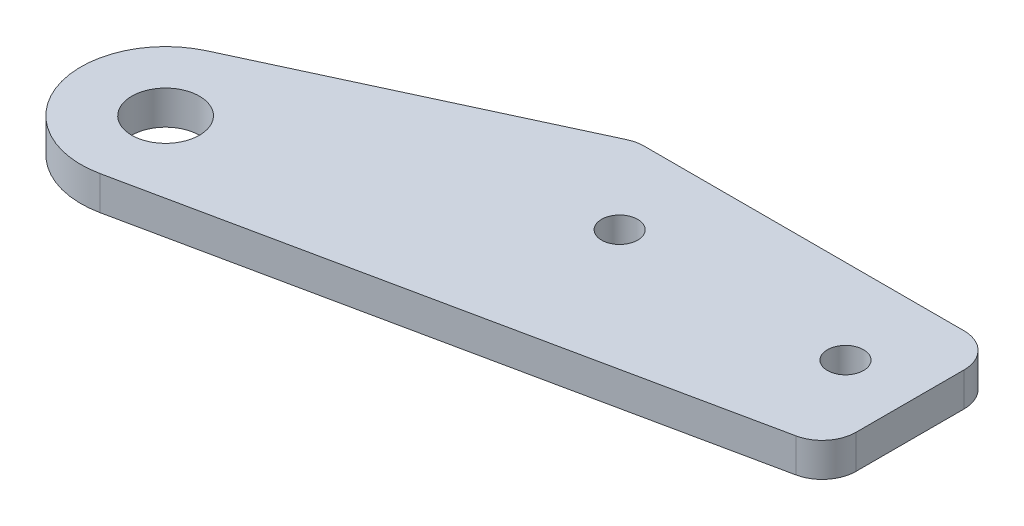
SolidWorks part; units mm, degrees
material "Thornel Mat VMA"
ref_plane "前视基准面" through (0, 0, 0) normal (0, 0, 1) x (1, 0, 0)
ref_plane "上视基准面" through (0, 0, 0) normal (0, 1, 0) x (1, 0, 0)
ref_plane "右视基准面" through (0, 0, 0) normal (1, 0, 0) x (0, 0, -1)
sketch "草图1" plane through (0, 0, 0) normal (0, 1, 0) x (1, 0, 0)
  line L0 (0, 15) -> (-26.0045, 2.9444)
  line L1 (0, 0) -> (32, 0)
  line L2 (0, 0) -> (0, 15)
  line L3 (0, 15) -> (32, 15)
  line L4 (32, 0) -> (32, 15)
  line L5 (32, 0) -> (-21.3079, -11.1998)
  line L6 (0, 7.5) -> (6, 7.5) construction
  line L7 (6, 7.5) -> (26, 7.5) construction
  line L8 (26, 7.5) -> (32, 7.5) construction
  circle A0 centre (-22.85, -3.86) radius 3
  circle A1 centre (-22.85, -3.86) radius 7.5
  circle A2 centre (6, 7.5) radius 1.6
  circle A3 centre (26, 7.5) radius 1.6
  dimension "D1" = 6
  dimension "D6" = 15
  dimension "D8" = 3.2
  dimension "D2" = 22.85
  dimension "D3" = 3.86
  dimension "D4" = 15
  dimension "D5" = 32
  dimension "D7" = 6
extrude "凸台-拉伸1" add sketch "草图1" along normal blind 3 contours A1 A0 | A1 L5 L1 L2 L0 | L1 L4 L3 L2 A3 A2
fillet "圆角1" radius 3 3 edges at (0, 1.5, -15) (32, 1.5, 0) (32, 1.5, -15)
